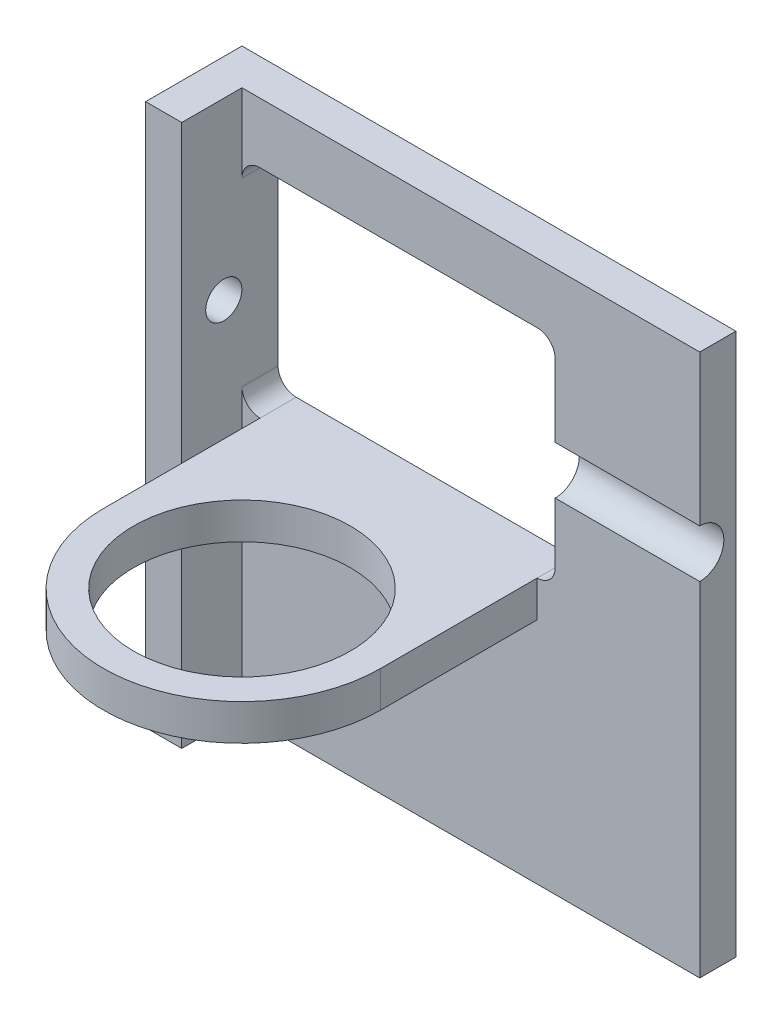
SolidWorks part; units mm, degrees
ref_plane "Front Plane" through (0, 0, 0) normal (0, 0, 1) x (1, 0, 0)
ref_plane "Top Plane" through (0, 0, 0) normal (0, 1, 0) x (1, 0, 0)
ref_plane "Right Plane" through (0, 0, 0) normal (1, 0, 0) x (0, 0, -1)
sketch "Sketch1" plane through (0, 0, 0) normal (0, 0, 1) x (1, 0, 0)
  line L1 (0, 0) -> (41, 0)
  line L2 (0, 0) -> (0, -45)
  line L3 (0, -45) -> (41, -45)
  line L4 (41, 0) -> (41, -45)
  line L5 (27.5, -23) -> (4.5, -23)
  line L6 (29, -21.5) -> (29, -6.5)
  line L7 (27.5, -5) -> (4.5, -5)
  line L8 (3, -21.5) -> (3, -6.5)
  arc A0 (4.5, -5) -> (3, -6.5) centre (4.5, -6.5) ccw
  arc A1 (4.5, -23) -> (3, -21.5) centre (4.5, -21.5) cw
  arc A2 (29, -21.5) -> (27.5, -23) centre (27.5, -21.5) cw
  arc A3 (29, -6.5) -> (27.5, -5) centre (27.5, -6.5) ccw
  point P13 (3, -23)
  point P16 (29, -23)
  point P19 (29, -5)
  dimension "D7" = 1.5
  dimension "D1" = 41
  dimension "D2" = 45
  dimension "D3" = 12
  dimension "D4" = 5
  dimension "D5" = 18
  dimension "D6" = 26
extrude "Boss-Extrude1" add sketch "Sketch1" along normal blind 3
sketch "Sketch2" plane through (0, 0, 0) normal (1, 0, 0) x (0, 0, -1)
  line L0 (-3, -14.5) -> (-8, -14.5) construction
  line L1 (-3, 0) -> (-8, 0)
  line L2 (-3, 0) -> (-3, -45)
  line L3 (-3, -45) -> (-8, -45)
  line L4 (-8, 0) -> (-8, -45)
  circle A1 centre (-4.51, -14.5) radius 1.5
  dimension "D3" = 3
  dimension "D4" = 14.5
  dimension "D1" = 5
  dimension "D2" = 45
  dimension "D5" = 1.51
extrude "Boss-Extrude2" add sketch "Sketch2" along normal blind 3
ref_plane "Plane1" through (0, -23, 0) normal (0, 1, 0) x (1, 0, 0)
sketch "Sketch4" plane through (0, -23, 0) normal (0, 1, 0) x (1, 0, 0)
  line L1 (27.5, -3) -> (4.5, -3)
  line L2 (27.5, -3) -> (27.5, -16)
  line L4 (27.5, 0) -> (4.5, 0)
  line L5 (4.5, 0) -> (4.5, -3)
  line L6 (4.5, -3) -> (27.5, -3)
  line L7 (27.5, -3) -> (27.5, 0)
  line L8 (27.5, 0) -> (4.5, 0)
  line L9 (4.5, 0) -> (4.5, -3)
  line L10 (4.5, -3) -> (27.5, -3)
  line L11 (27.5, -3) -> (27.5, 0)
  line L12 (4.5, -3) -> (4.5, -16)
  arc A0 (4.5, -16) -> (27.5, -16) centre (16, -16) ccw
  circle A1 centre (16, -16) radius 9
  dimension "D3" = 18
  dimension "D4" = 11.5
  dimension "D2" = 13
  dimension "D1" = 0
extrude "Boss-Extrude3" add sketch "Sketch4" against normal blind 3 contours L12 A0 L2 L1 A1
sketch "Sketch7" plane through (41, 0, 0) normal (1, 0, 0) x (0, 0, -1)
  line L0 (-3, 0) -> (-3, -14.5) construction
  line L1 (-3, -45) -> (-3, 0) construction
  line L2 (-3, -12.5) -> (-3, -16.5) construction
  line L3 (-3, -12.5) -> (-3, -16.5)
  arc A0 (-3, -16.5) -> (-3, -12.5) centre (-3, -14.5) ccw
  dimension "D2" = 4
  dimension "D1" = 14.5
extrude "Cut-Extrude4" cut sketch "Sketch7" against normal up to surface (12 mm away) contours L3 A0 up to face at (29, -14, 1.5)
